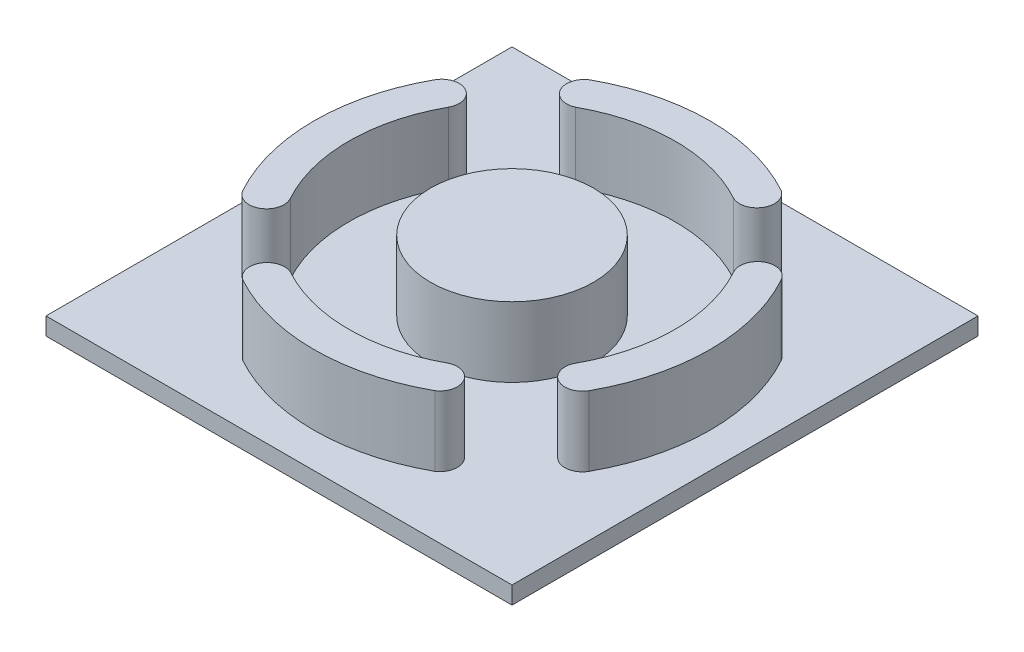
SolidWorks part; units mm, degrees
ref_plane "Front Plane" through (0, 0, 0) normal (0, 0, 1) x (1, 0, 0)
ref_plane "Top Plane" through (0, 0, 0) normal (0, 1, 0) x (1, 0, 0)
ref_plane "Right Plane" through (0, 0, 0) normal (1, 0, 0) x (0, 0, -1)
sketch "Sketch1" plane through (0, 0, 0) normal (0, 1, 0) x (1, 0, 0)
  line L0 (20, 0) -> (-20, 0)
  line L1 (-20, 0) -> (-20, 40)
  line L2 (-20, 40) -> (20, 40)
  line L3 (20, 40) -> (20, 0)
  point P5 (0, 0)
  dimension "D1" = 40
  dimension "D2" = 40
extrude "Boss-Extrude1" add sketch "Sketch1" along normal blind 1.5
sketch "Sketch2" plane through (0, 1.5, 0) normal (0, 1, 0) x (1, 0, 0)
  line L0 (-20, 20) -> (44.158, 20) construction
  line L1 (-20, 40) -> (-20, 0) construction
  line L2 (0, 40) -> (0, -0.9281) construction
  line L3 (20, 40) -> (-20, 40) construction
  circle A0 centre (0, 20) radius 7
  arc A1 (-6.7873, 32.2447) -> (6.7873, 32.2447) centre (0, 20) cw
  arc A2 (-8.2418, 34.8685) -> (8.2418, 34.8685) centre (0, 20) cw
  arc A3 (-8.2418, 34.8685) -> (-6.7873, 32.2447) centre (-7.4159, 33.6113) ccw
  arc A4 (8.2418, 34.8685) -> (6.7873, 32.2447) centre (7.4159, 33.6113) cw
  arc A5 (-8.2418, 5.1315) -> (8.2418, 5.1315) centre (0, 20) ccw
  arc A6 (-8.2418, 5.1315) -> (-6.7873, 7.7553) centre (-7.4159, 6.3887) cw
  arc A7 (-6.7873, 7.7553) -> (6.7873, 7.7553) centre (0, 20) ccw
  arc A8 (8.2418, 5.1315) -> (6.7873, 7.7553) centre (7.4159, 6.3887) ccw
  arc A9 (12.2447, 26.7873) -> (12.2447, 13.2127) centre (0, 20) cw
  arc A10 (14.8685, 28.2418) -> (14.8685, 11.7582) centre (0, 20) cw
  arc A11 (12.2447, 26.7873) -> (14.8685, 28.2418) centre (13.5566, 27.5145) cw
  arc A12 (12.2447, 13.2127) -> (14.8685, 11.7582) centre (13.5566, 12.4855) ccw
  arc A13 (-12.2447, 26.7873) -> (-12.2447, 13.2127) centre (0, 20) ccw
  arc A14 (-12.2447, 26.7873) -> (-14.8685, 28.2418) centre (-13.5566, 27.5145) ccw
  arc A15 (-14.8685, 28.2418) -> (-14.8685, 11.7582) centre (0, 20) ccw
  arc A16 (-12.2447, 13.2127) -> (-14.8685, 11.7582) centre (-13.5566, 12.4855) cw
  dimension "D1" = 14
  dimension "D2" = 14
  dimension "D4" = 17
  dimension "D5" = 1.5042
  dimension "D7" = 14
  dimension "D9" = 17
  dimension "D10" = 58
  dimension "D11" = 1.5
  dimension "D3" = 58
  dimension "D6" = 58
  dimension "D8" = 58
extrude "Boss-Extrude2" add sketch "Sketch2" along normal blind 6
